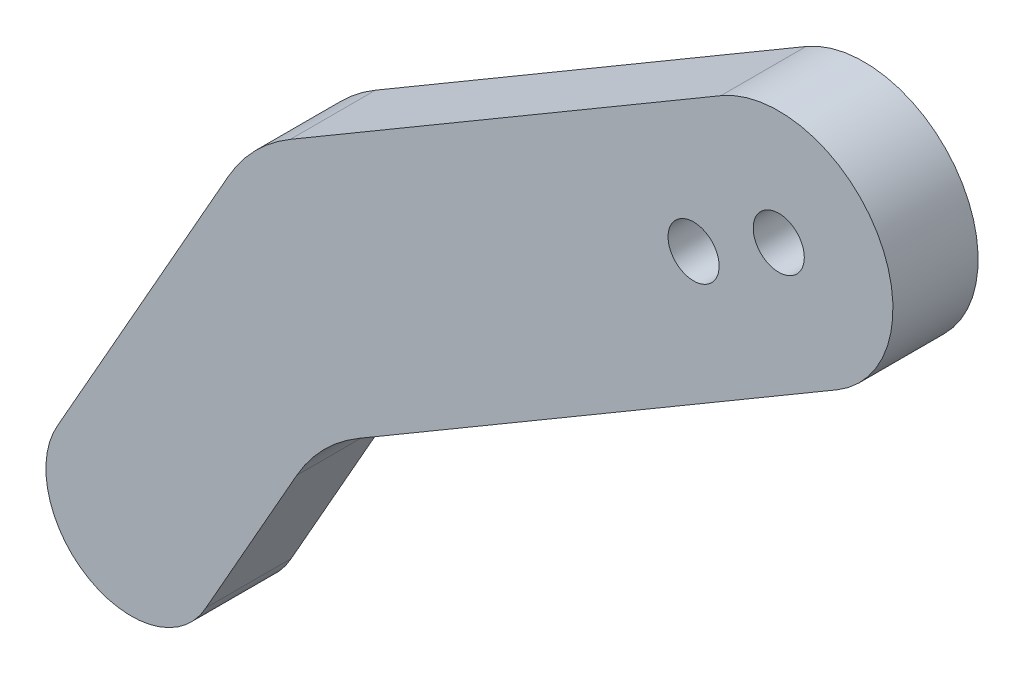
SolidWorks part; units mm, degrees
ref_plane "Front Plane" through (0, 0, 0) normal (0, 0, 1) x (1, 0, 0)
ref_plane "Top Plane" through (0, 0, 0) normal (0, 1, 0) x (1, 0, 0)
ref_plane "Right Plane" through (0, 0, 0) normal (1, 0, 0) x (0, 0, -1)
sketch "Sketch3" plane through (0, 0, 0) normal (0, 0, 1) x (1, 0, 0)
  line L0 (0, 0) -> (10.022, 17.6772)
  line L1 (0, 0) -> (8.6992, -4.932) construction
  line L2 (8.6992, -4.932) -> (14.0358, 4.481)
  line L3 (13.6535, 21.366) -> (38.9301, 36.2248)
  line L4 (38.9301, 36.2248) -> (45.726, 24.6641) construction
  line L5 (17.6673, 8.1698) -> (45.726, 24.6641)
  arc A0 (38.9301, 36.2248) -> (45.726, 24.6641) centre (42.328, 30.4445) cw
  arc A1 (0, 0) -> (8.6992, -4.932) centre (4.3053, -2.5441) ccw
  arc A2 (10.022, 17.6772) -> (13.6535, 21.366) centre (18.7212, 12.7452) cw
  arc A3 (14.0358, 4.481) -> (17.6673, 8.1698) centre (22.735, -0.451) cw
  point P10 (11.3435, 20.0081)
  point P13 (19.9017, -5.697)
  point P15 (15.3573, 6.8119)
  dimension "D7" = 5.0008
  dimension "D8" = 10
  dimension "D9" = 10
  dimension "D1" = 23
  dimension "D2" = 32
  dimension "D3" = 150
  dimension "D5" = 13.5
  dimension "D6" = 10
extrude "Boss-Extrude1" add sketch "Sketch3" along normal blind 5 contours L0 A1 L2 L5 A0 L3
sketch "Sketch4" plane through (0, 0, 5) normal (0, 0, 1) x (1, 0, 0)
  line L0 (38.9301, 36.2248) -> (45.726, 24.6641) construction
  line L1 (42.328, 30.4445) -> (24.0382, 19.6928) construction
  line L2 (38.9301, 36.2248) -> (45.726, 24.6641) construction
  circle A0 centre (42.328, 30.4445) radius 1.5
  arc A1 (45.726, 24.6641) -> (38.9301, 36.2248) centre (42.328, 30.4445) ccw construction
  circle A2 centre (37.328, 27.5052) radius 1.5
  point P9 (42.328, 30.4445)
  dimension "D1" = 3
  dimension "D2" = 5
  dimension "D3" = 3
extrude "Cut-Extrude1" cut sketch "Sketch4" against normal blind 7
